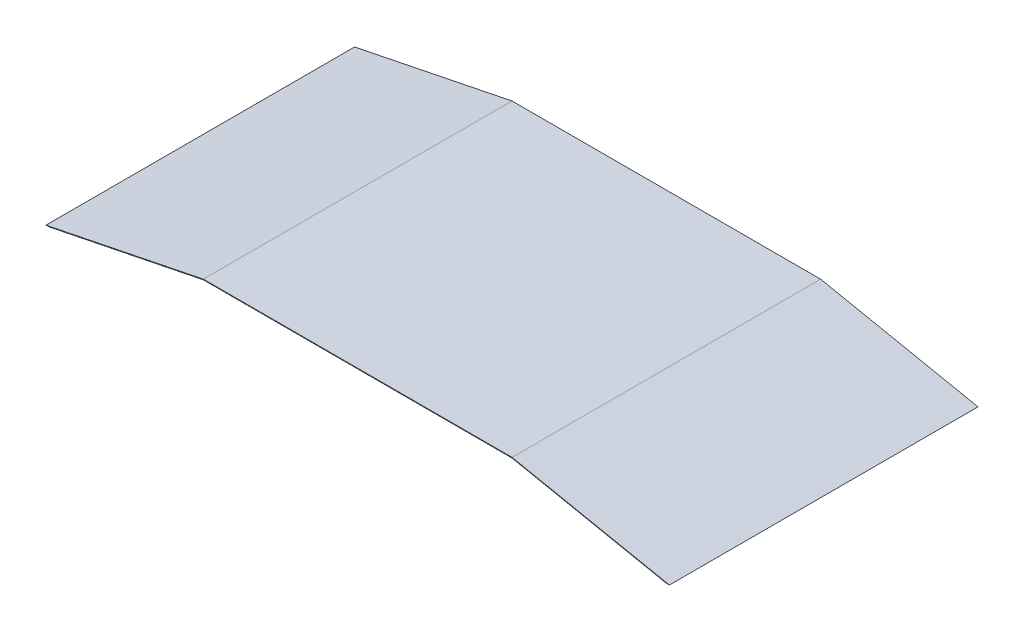
SolidWorks part; units mm, degrees
ref_plane "前视基准面" through (0, 0, 0) normal (0, 0, 1) x (1, 0, 0)
ref_plane "上视基准面" through (0, 0, 0) normal (0, 1, 0) x (1, 0, 0)
ref_plane "右视基准面" through (0, 0, 0) normal (1, 0, 0) x (0, 0, -1)
other "Configuration Table"
sketch "草图1" plane through (0, 0, 0) normal (0, 0, 1) x (1, 0, 0)
  line L0 (0, 0) -> (0, 77.2574) construction
  line L1 (0, 0) -> (-100, 0) construction
  line L2 (-100, 0) -> (-50, 10.1355)
  line L3 (-50, 10.1355) -> (50, 10.1355)
  line L4 (101, 0) -> (50, 10.3382)
  line L5 (100, 0) -> (101, 0)
  line L6 (-100, 0) -> (-101, 0)
  line L7 (-101, 0) -> (-50, 10.3382)
  line L9 (50, 10.3382) -> (-50, 10.3382)
  line L10 (100, 0) -> (50, 10.1355)
  point P7 (0, 10.3382)
  point P17 (0, 10.1355)
  dimension "D1" = 11.459
  dimension "D2" = 50
  dimension "D3" = 50
  dimension "D4" = 1
extrude "凸台-拉伸1" add sketch "草图1" along normal blind 100
